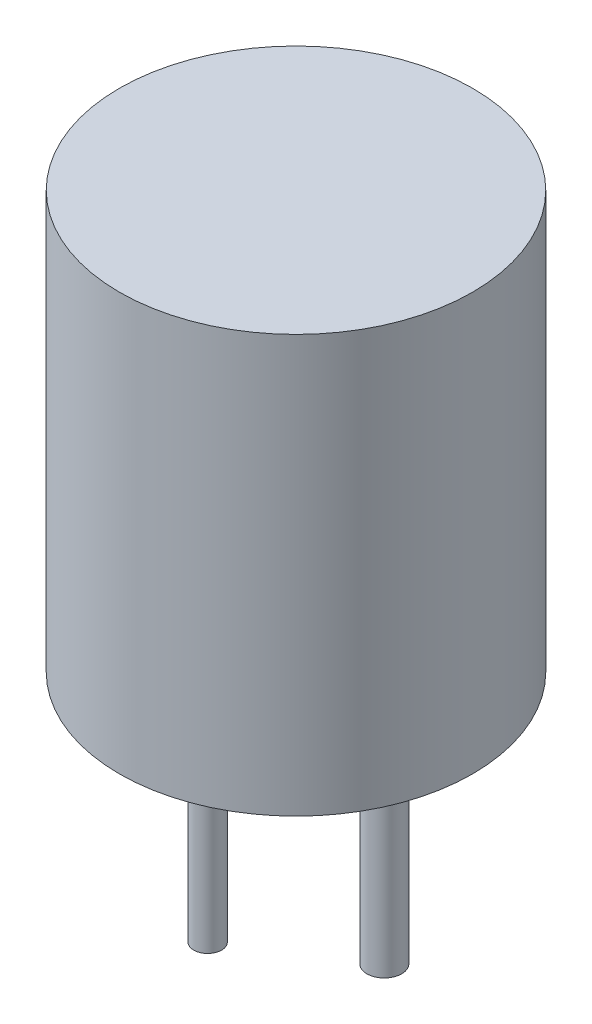
SolidWorks part; units mm, degrees
ref_plane "前视基准面" through (0, 0, 0) normal (0, 0, 1) x (1, 0, 0)
ref_plane "上视基准面" through (0, 0, 0) normal (0, 1, 0) x (1, 0, 0)
ref_plane "右视基准面" through (0, 0, 0) normal (1, 0, 0) x (0, 0, -1)
sketch "草图1" plane through (0, 0, 0) normal (0, 1, 0) x (1, 0, 0)
  circle A0 centre (0, 0) radius 5.08
  dimension "D1" = 10.16
extrude "拉伸1" add sketch "草图1" along normal blind 12
sketch "草图2" plane through (0, 0, 0) normal (0, -1, 0) x (1, 0, 0)
  line L0 (4.8023, 0) -> (-11.2367, 0) construction
  circle A0 centre (-2.54, 0) radius 0.4
  dimension "D2" = 0.8
  dimension "D1" = 2.54
extrude "拉伸2" add sketch "草图2" along normal blind 8
sketch "草图3" plane through (0, 0, 0) normal (0, -1, 0) x (1, 0, 0)
  line L0 (7.1249, 0) -> (-2.8562, 0) construction
  circle A0 centre (2.54, 0) radius 0.5
  dimension "D1" = 1
  dimension "D2" = 2.54
extrude "拉伸3" add sketch "草图3" along normal blind 6
